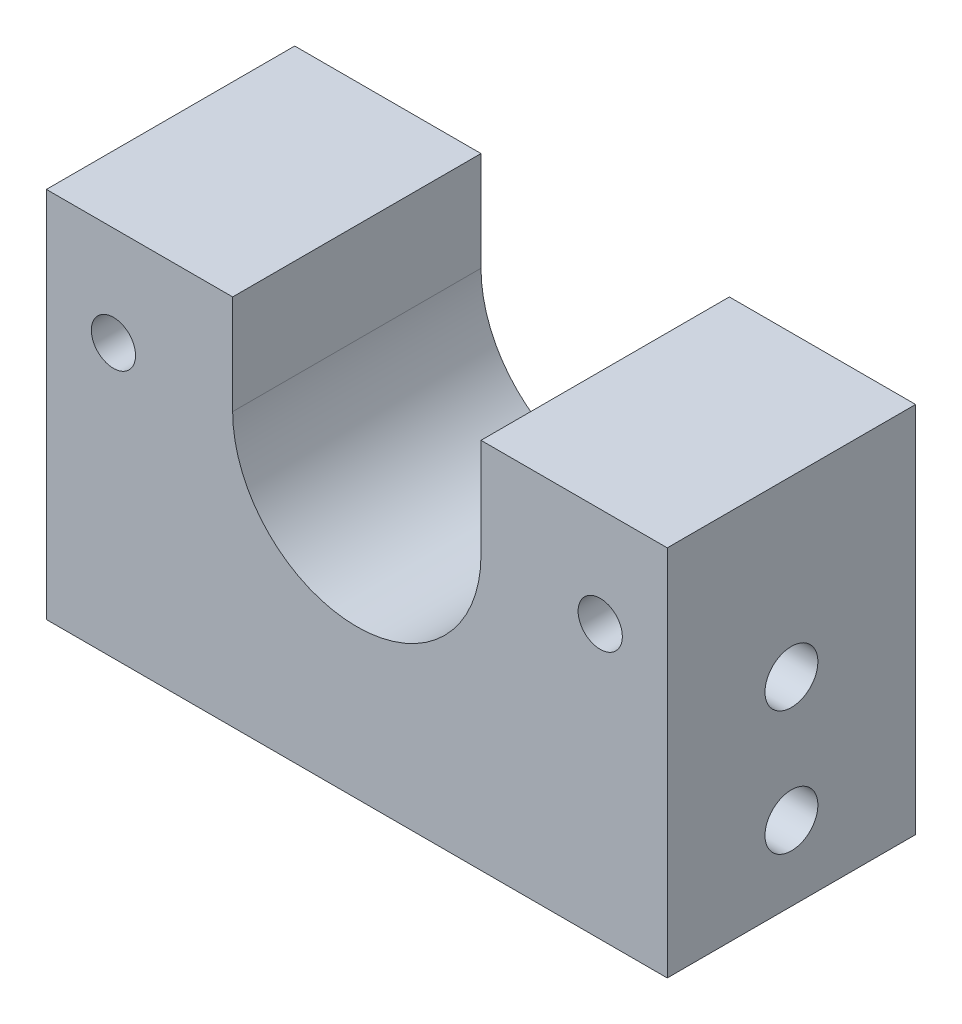
SolidWorks part; units mm, degrees
material "ABS PC"
ref_plane "Front Plane" through (0, 0, 0) normal (0, 0, 1) x (1, 0, 0)
ref_plane "Top Plane" through (0, 0, 0) normal (0, 1, 0) x (1, 0, 0)
ref_plane "Right Plane" through (0, 0, 0) normal (1, 0, 0) x (0, 0, -1)
sketch "Sketch1" plane through (0, 0, 0) normal (1, 0, 0) x (0, 0, -1)
  line L1 (0, 0) -> (12.7, 0)
  line L2 (0, 0) -> (0, 19.05)
  line L3 (0, 19.05) -> (12.7, 19.05)
  line L4 (12.7, 0) -> (12.7, 19.05)
  dimension "D1" = 12.7
  dimension "D2" = 19.05
extrude "Base" add sketch "Sketch1" against normal blind 31.75
hole_wizard "MountingHoles" positions "Sketch4" profile "Sketch3" tap size "#6-32" standard "ANSI Inch"
sketch "Sketch4" plane through (23.2872, 0, 3.1883) normal (0, 1, 0) x (1, 0, 0)
  line L0 (-23.2872, 15.8883) -> (-23.2872, 3.1883) construction
  line L3 (-23.2872, 9.5383) -> (-55.0372, 9.5383) construction
  line L4 (-55.0372, 15.8883) -> (-55.0372, 3.1883) construction
  line L5 (-55.0372, 3.1883) -> (-55.0372, 15.8883) construction
  point P0 (-29.6372, 9.5383)
  point P2 (-48.6872, 9.5383)
  dimension "D1" = 6.35
  dimension "D2" = 6.35
sketch "Sketch3" plane through (-6.35, 0, -6.35) normal (1, 0, 0) x (0, 0, -1)
  line L0 (0, 0) -> (0, 13.5127)
  line L1 (0, 13.5127) -> (1.3525, 12.7)
  line L2 (1.3525, 12.7) -> (1.3525, 10.795)
  line L3 (1.3525, 10.795) -> (1.7526, 10.795)
  line L4 (1.7526, 10.795) -> (1.7526, 0)
  line L5 (1.7526, 0) -> (0, 0)
  line L10 (0, 13.5127) -> (-1.3526, 12.7) construction
  line L11 (0, -6.35) -> (0, 107.95) construction
  dimension "Tap Drill Dia." = 2.7051
  dimension "Tap Drill Depth" = 12.7
  dimension "Thread Major Dia." = 3.5052
  dimension "Thread Depth" = 10.795
  dimension "Drill Angle" = 118
sketch "Sketch5" plane through (0, 0, -12.7) normal (0, 0, -1) x (-1, 0, 0)
  line L0 (31.75, 19.05) -> (0, 19.05) construction
  line L2 (31.75, 19.05) -> (0, 19.05) construction
  line L6 (15.875, 5.08) -> (15.875, 28.2578) construction
  line L7 (15.875, 19.05) -> (15.875, 13.97) construction
  line L8 (22.225, 19.05) -> (22.225, 13.97)
  line L9 (9.525, 19.05) -> (9.525, 13.97)
  arc A2 (22.225, 19.05) -> (9.525, 19.05) centre (15.875, 19.05) ccw
  arc A3 (9.525, 13.97) -> (22.225, 13.97) centre (15.875, 13.97) ccw
  point P1 (15.875, 19.05)
  point P18 (15.875, 16.51)
  dimension "D3" = 5.08
  dimension "D2" = 12.7
extrude "MotorSlot" cut sketch "Sketch5" against normal through all
hole_wizard "MotorHoles" positions "Sketch11" profile "Sketch10" tap size "#4-40" standard "ANSI Inch" end condition through all
sketch "Sketch11" plane through (0, 0, -12.7) normal (0, 0, -1) x (-1, 0, 0)
  line L0 (15.875, 13.97) -> (15.875, 37.9737) construction
  arc A0 (9.525, 13.97) -> (22.225, 13.97) centre (15.875, 13.97) ccw construction
  point P0 (3.429, 13.97)
  point P2 (28.321, 13.97)
  dimension "D1" = 24.892
sketch "Sketch10" plane through (-3.429, 13.97, -12.7) normal (1, 0, 0) x (0, 1, 0)
  line L0 (0, 0) -> (0, 12.7)
  line L1 (0, 12.7) -> (1.1303, 12.7)
  line L2 (1.1303, 12.7) -> (1.1303, 0)
  line L5 (1.1303, 0) -> (0, 0)
  line L11 (0, -6.35) -> (0, 107.95) construction
  dimension "Thru Tap Drill Dia." = 2.2606
  dimension "Thru Tap Drill Depth" = 12.7
cosmetic thread "Hole Thread3" parameters "D2"=2.8448
cosmetic thread "Hole Thread4" parameters "D2"=2.8448
hole_wizard "#6-32 Tapped Hole1" positions "Sketch13" profile "Sketch12" tap size "#6-32" standard "ANSI Inch"
sketch "Sketch13" plane through (0, 0, 0) normal (1, 0, 0) x (0, 0, -1)
  line L0 (6.35, 0) -> (6.35, 19.05) construction
  line L1 (0, 0) -> (12.7, 0) construction
  line L2 (12.7, 19.05) -> (0, 19.05) construction
  point P0 (6.35, 3.81)
  point P2 (6.35, 10.16)
  dimension "D1" = 3.81
  dimension "D2" = 10.16
sketch "Sketch12" plane through (0, 3.81, -6.35) normal (0, 1, 0) x (0, 0, -1)
  line L0 (0, 0) -> (0, 9.1947)
  line L1 (0, 9.1947) -> (1.3525, 8.382)
  line L2 (1.3525, 8.382) -> (1.3525, 0)
  line L5 (1.3525, 0) -> (0, 0)
  line L10 (0, 9.1947) -> (-1.3526, 8.382) construction
  line L11 (0, -6.35) -> (0, 107.95) construction
  dimension "Tap Drill Dia." = 2.7051
  dimension "Tap Drill Depth" = 8.382
  dimension "Drill Angle" = 118
cosmetic thread "Hole Thread5" parameters "D1"=8.382, "D2"=3.5052
cosmetic thread "Hole Thread6" parameters "D1"=8.382, "D2"=3.5052
